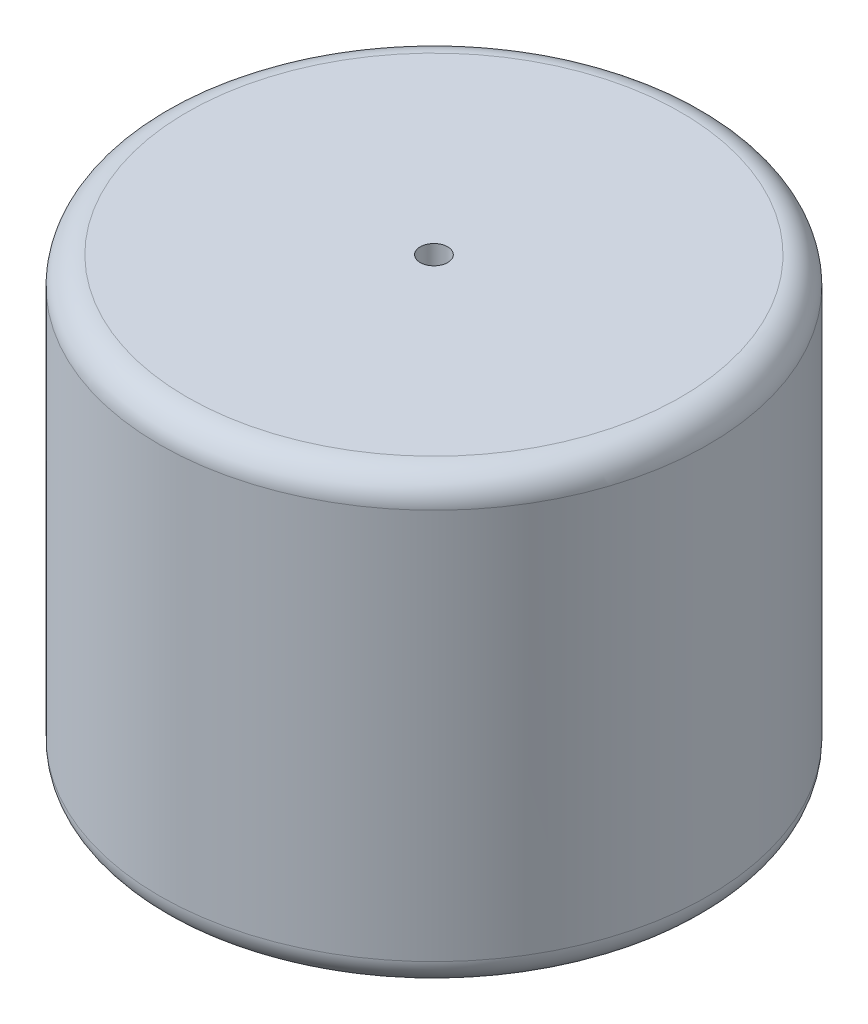
SolidWorks part; units mm, degrees
ref_plane "Front Plane" through (0, 0, 0) normal (0, 0, 1) x (1, 0, 0)
ref_plane "Top Plane" through (0, 0, 0) normal (0, 1, 0) x (1, 0, 0)
ref_plane "Right Plane" through (0, 0, 0) normal (1, 0, 0) x (0, 0, -1)
sketch "Sketch1" plane through (0, 0, 0) normal (0, 1, 0) x (1, 0, 0)
  circle A0 centre (0, 0) radius 20
extrude "Boss-Extrude1" add sketch "Sketch1" against normal blind 7.5
sketch "Sketch2" plane through (0, -7.5, 0) normal (0, -1, 0) x (1, 0, 0)
  circle A0 centre (0, 0) radius 12.5
  circle A1 centre (0, 0) radius 20 construction
  circle A2 centre (0, 0) radius 20
extrude "Boss-Extrude2" add sketch "Sketch2" along normal blind 15
ref_plane "Plane1" through (0, -22.5, 0) normal (0, -1, 0) x (-1, 0, 0)
sketch "Sketch3" plane through (0, -22.5, 0) normal (0, -1, 0) x (1, 0, 0)
  circle A0 centre (0, 0) radius 20 construction
  circle A1 centre (0, 0) radius 20
extrude "Boss-Extrude3" add sketch "Sketch3" along normal blind 10
sketch "Sketch4" plane through (0, -22.5, 0) normal (0, -1, 0) x (-1, 0, 0)
  line L1 (10.1645, 5.4787) -> (0.3376, 11.5421)
  line L2 (0.3376, 11.5421) -> (-9.8269, 6.0634)
  line L3 (-9.8269, 6.0634) -> (-10.1645, -5.4787)
  line L4 (-10.1645, -5.4787) -> (-0.3376, -11.5421)
  line L5 (-0.3376, -11.5421) -> (9.8269, -6.0634)
  line L6 (9.8269, -6.0634) -> (10.1645, 5.4787)
  circle A0 centre (0, 0) radius 10 construction
extrude "Cut-Extrude2" cut sketch "Sketch4" along normal blind 5
sketch "Sketch5" plane through (0, 0, 0) normal (1, 0, 0) x (0, 0, -1)
  line L0 (0, -32.5) -> (0, 0) construction
  line L2 (-20, -32.5) -> (20, -32.5) construction
  line L3 (7.5, -17.5) -> (12.5, -17.5)
  line L5 (-7.5, -17.5) -> (-7.5, -32.5)
  line L6 (-7.5, -32.5) -> (7.5, -32.5)
  line L7 (7.5, -17.5) -> (7.5, -32.5)
  line L8 (-7.5, -17.5) -> (7.5, -32.5) construction
  line L9 (-7.5, -32.5) -> (7.5, -17.5) construction
  line L10 (-12.5, -7.5) -> (12.5, -7.5)
  line L11 (-12.5, -7.5) -> (-12.5, -17.5)
  line L12 (-12.5, -17.5) -> (-7.5, -17.5)
  line L13 (12.5, -7.5) -> (12.5, -17.5)
  line L14 (-12.5, -7.5) -> (12.5, -17.5) construction
  line L15 (-12.5, -17.5) -> (12.5, -7.5) construction
  point P5 (0, -25)
  point P11 (0, -12.5)
  dimension "D1" = 15
  dimension "D2" = 10
  dimension "D3" = 15
  dimension "D4" = 25
extrude "Cut-Extrude3" cut sketch "Sketch5" against normal through all
sketch "Sketch6" plane through (0, -32.5, 0) normal (0, -1, 0) x (1, 0, 0)
  circle A0 centre (0, 0) radius 8
extrude "Cut-Extrude4" cut sketch "Sketch6" against normal blind 5
sketch "Sketch7" plane through (0, -7.5, 0) normal (0, -1, 0) x (1, 0, 0)
  circle A0 centre (0, 0) radius 2.1
extrude "Cut-Extrude5" cut sketch "Sketch7" against normal blind 4.5
sketch "Sketch8" plane through (0, -3, 0) normal (0, -1, 0) x (1, 0, 0)
  circle A0 centre (0, 0) radius 1
  dimension "D1" = 2
extrude "Cut-Extrude6" cut sketch "Sketch8" against normal through all
fillet "Fillet1" radius 1.5 1 edges at (0, -7.5, -2.1)
fillet "Fillet2" radius 2 2 edges at (20, -32.5, 0) (0, 0, 20)
